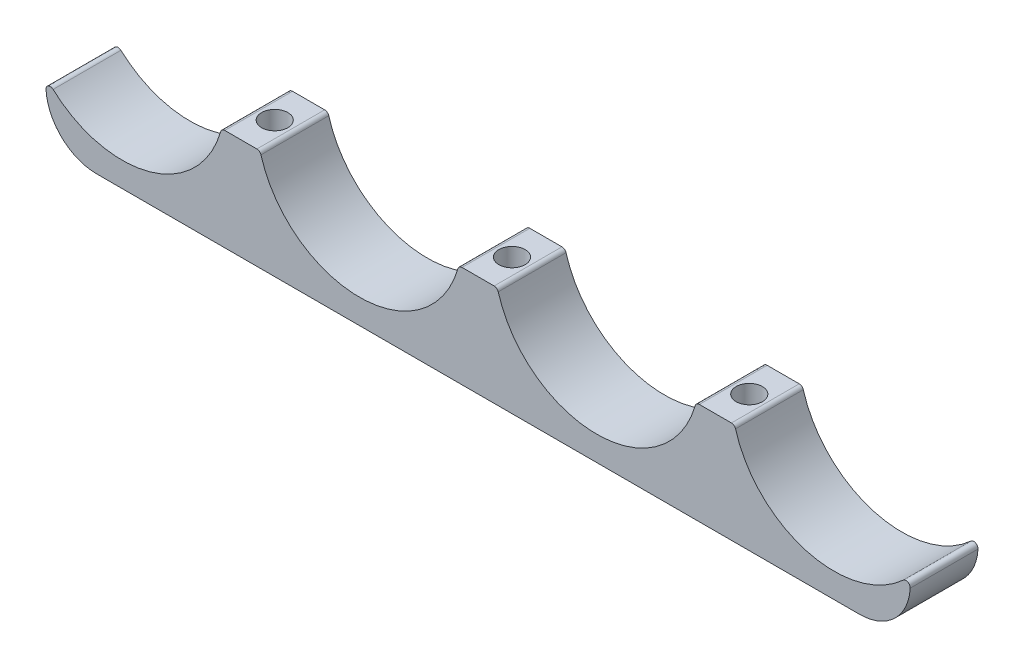
SolidWorks part; units mm, degrees
material "ABS"
ref_plane "Front" through (0, 0, 0) normal (0, 0, 1) x (1, 0, 0)
ref_plane "Top" through (0, 0, 0) normal (0, 1, 0) x (1, 0, 0)
ref_plane "Right" through (0, 0, 0) normal (1, 0, 0) x (0, 0, -1)
sketch "Esquisse1" plane through (0, 0, 0) normal (0, 0, 1) x (1, 0, 0)
  line L0 (0, -50) -> (0, 50) construction
  line L1 (-30.2778, 12) -> (-25.7222, 12)
  line L2 (-51, 6.9124) -> (-51, 0)
  line L3 (-51, 0) -> (51, 0)
  line L4 (51, 6.9124) -> (51, 0)
  line L5 (-2.2778, 12) -> (2.2778, 12)
  line L6 (25.7222, 12) -> (30.2778, 12)
  arc A0 (-51, 6.9124) -> (-30.2778, 12) centre (-42, 15) ccw
  arc A1 (-25.7222, 12) -> (-2.2778, 12) centre (-14, 15) ccw
  arc A3 (25.7222, 12) -> (2.2778, 12) centre (14, 15) cw
  arc A4 (51, 6.9124) -> (30.2778, 12) centre (42, 15) cw
  dimension "D1" = 28
  dimension "D2" = 28
  dimension "D3" = 24.2
  dimension "D4" = 15
  dimension "D5" = 3
  dimension "D6" = 9
extrude "Boss.-Extru.1" add sketch "Esquisse1" along normal mid plane 8
fillet "Congé1" radius 6 2 edges at (51, 0, 0) (-51, 0, 0)
fillet "Congé2" radius 0.5 8 edges at (51, 6.9124, 0) (30.2778, 12, 0) (25.7222, 12, 0) (2.2778, 12, 0) (-2.2778, 12, 0) (-25.7222, 12, 0) (-30.2778, 12, 0) (-51, 6.9124, 0)
sketch "Esquisse2" plane through (0, 0, 0) normal (0, 0, 1) x (1, 0, 0)
  line L0 (-28, 12) -> (-28, 0)
  line L1 (-26.1041, 12) -> (-29.8959, 12) construction
  line L2 (-45, 0) -> (45, 0) construction
  line L3 (-28, 0) -> (-24.9, 0)
  line L4 (-24.9, 0) -> (-24.9, 5.8)
  line L5 (-24.9, 5.8) -> (-26.1, 5.8)
  line L6 (-26.1, 5.8) -> (-26.1, 9)
  line L7 (-26.1, 9) -> (-26.45, 9)
  line L8 (-26.45, 9) -> (-26.45, 12)
  line L9 (-26.45, 12) -> (-28, 12)
  line L10 (-28, 0) -> (-28, -3.1) construction
  arc A0 (-50.1544, 6.0604) -> (-30.3762, 11.6389) centre (-42, 15) ccw construction
  dimension "D1" = 6.2
  dimension "D2" = 3.1
  dimension "D3" = 3.8
  dimension "D4" = 6
  dimension "D5" = 3.2
revolve "Enlèvement de matière-Révolution1" cut sketch "Esquisse2" angle 360 about L10
pattern_linear "Répétition linéaire1" count 3 spacing 28 along (1, 0, 0) of "Enlèvement de matière-Révolution1"
